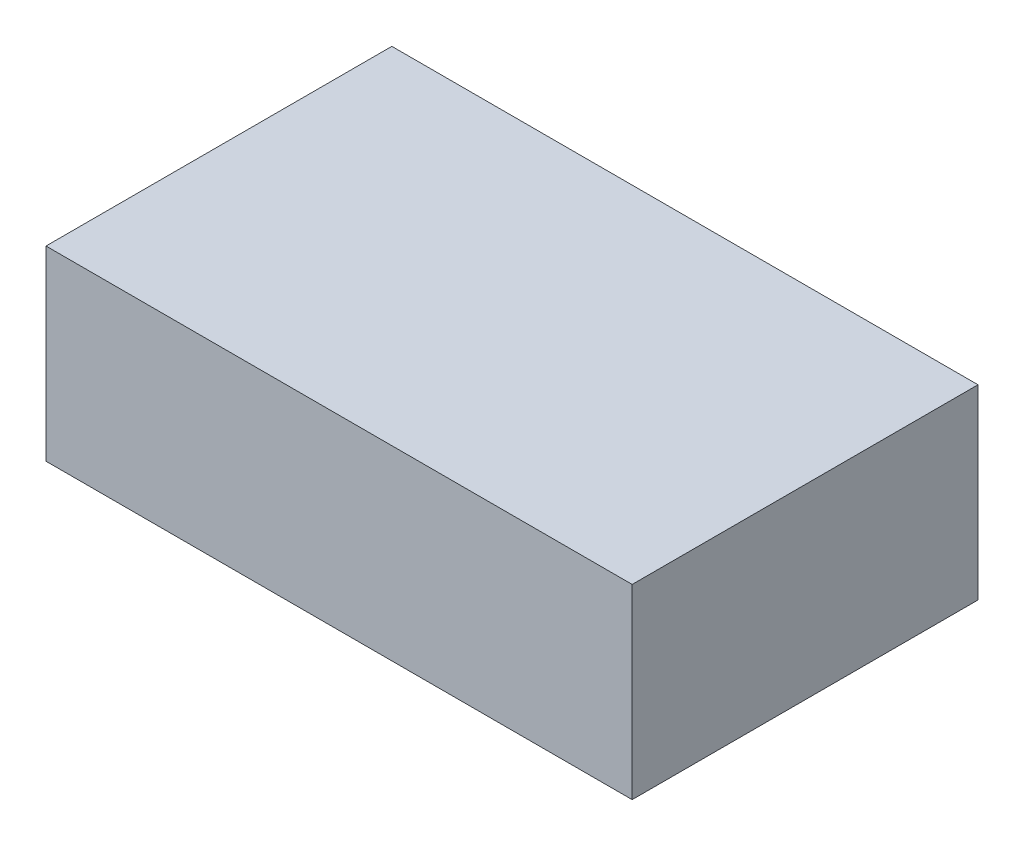
SolidWorks part; units mm, degrees
ref_plane "Front Plane" through (0, 0, 0) normal (0, 0, 1) x (1, 0, 0)
ref_plane "Top Plane" through (0, 0, 0) normal (0, 1, 0) x (1, 0, 0)
ref_plane "Right Plane" through (0, 0, 0) normal (1, 0, 0) x (0, 0, -1)
sketch "Sketch1" plane through (0, 0, 0) normal (0, 1, 0) x (1, 0, 0)
  line L1 (0, 0) -> (10, 0)
  line L2 (0, 0) -> (0, -5.9)
  line L3 (0, -5.9) -> (10, -5.9)
  line L4 (10, 0) -> (10, -5.9)
  dimension "D1" = 10
  dimension "D2" = 5.9
extrude "Boss-Extrude1" add sketch "Sketch1" along normal blind 3.18
equation "\"D1@Boss-Extrude1\"=3.18"
